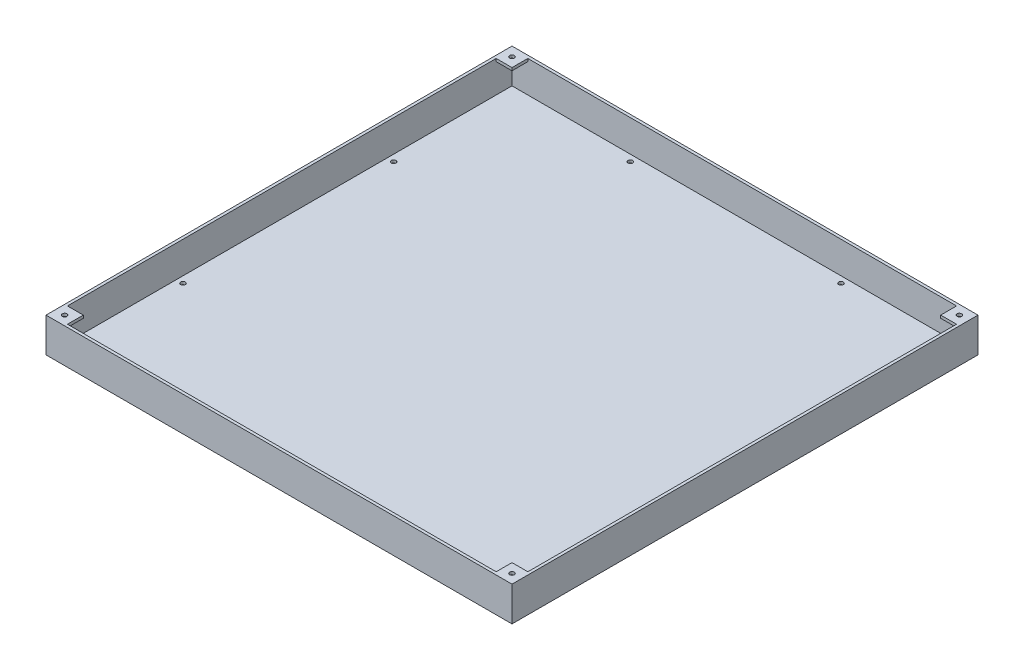
SolidWorks part; units mm, degrees
material "6063-O"
ref_plane "Front Plane" through (0, 0, 0) normal (0, 0, 1) x (1, 0, 0)
ref_plane "Top Plane" through (0, 0, 0) normal (0, 1, 0) x (1, 0, 0)
ref_plane "Right Plane" through (0, 0, 0) normal (1, 0, 0) x (0, 0, -1)
sketch "Sketch1" plane through (0, 0, 0) normal (0, 1, 0) x (1, 0, 0)
  line L1 (-250, 250) -> (250, 250)
  line L2 (-250, 250) -> (-250, -250)
  line L3 (-250, -250) -> (250, -250)
  line L4 (250, 250) -> (250, -250)
  line L5 (-250, 250) -> (250, -250) construction
  line L6 (-250, -250) -> (250, 250) construction
  point P0 (0, 0)
  dimension "D1" = 500
  dimension "D2" = 500
extrude "Boss-Extrude1" add sketch "Sketch1" along normal blind 37
shell "Shell1" thickness 3
sketch "Sketch3" plane through (0, 37, 0) normal (0, 1, 0) x (1, 0, 0)
  line L0 (-250, -250) -> (250, -250) construction
  line L1 (250, -250) -> (250, 250) construction
  line L2 (0, -250) -> (0, 250) construction
  line L3 (250, 250) -> (-250, 250) construction
  line L6 (-250, -250) -> (250, 250) construction
  line L7 (-250, 250) -> (250, -250) construction
  circle A0 centre (113, -240) radius 2.5
  circle A1 centre (-113, -240) radius 2.5
  circle A2 centre (240, 113) radius 2.5
  circle A3 centre (240, -113) radius 2.5
  circle A4 centre (-240, -113) radius 2.5
  circle A5 centre (-240, 113) radius 2.5
  circle A6 centre (-113, 240) radius 2.5
  circle A7 centre (113, 240) radius 2.5
  dimension "D1" = 5
  dimension "D2" = 10
  dimension "D3" = 137
extrude "Cut-Extrude1" cut sketch "Sketch3" against normal up to surface (37 mm away) up to face at (0, 0, 0)
sketch "Sketch4" plane through (0, 37, 0) normal (0, 1, 0) x (1, 0, 0)
  line L0 (0, 247) -> (0, 0) construction
  line L1 (-247, 247) -> (-230, 247)
  line L2 (-247, 247) -> (-247, 230)
  line L3 (-247, 230) -> (-230, 230)
  line L4 (-230, 247) -> (-230, 230)
  line L5 (247, 247) -> (-247, 247) construction
  line L6 (0, 0) -> (-247, 0) construction
  line L7 (-247, 247) -> (-247, -247) construction
  line L8 (247, 230) -> (230, 230)
  line L9 (230, 247) -> (230, 230)
  line L10 (247, 247) -> (230, 247)
  line L11 (247, 247) -> (247, 230)
  line L12 (247, -247) -> (247, -230)
  line L13 (247, -247) -> (230, -247)
  line L14 (230, -247) -> (230, -230)
  line L15 (247, -230) -> (230, -230)
  line L16 (-247, -230) -> (-230, -230)
  line L17 (-230, -247) -> (-230, -230)
  line L18 (-247, -247) -> (-230, -247)
  line L19 (-247, -247) -> (-247, -230)
  dimension "D1" = 17
  dimension "D2" = 17
extrude "Boss-Extrude2" add sketch "Sketch4" against normal blind 3
sketch "Sketch5" plane through (0, 37, 0) normal (0, 1, 0) x (1, 0, 0)
  line L0 (-230, 230) -> (-230, 247) construction
  line L1 (-247, 230) -> (-230, 230) construction
  line L2 (0, 247) -> (0, 0) construction
  line L3 (247, 247) -> (-247, 247) construction
  line L4 (0, 0) -> (-247, 0) construction
  line L5 (-247, 230) -> (-247, -230) construction
  circle A0 centre (-240, 240) radius 2.5
  circle A1 centre (240, 240) radius 2.5
  circle A2 centre (240, -240) radius 2.5
  circle A3 centre (-240, -240) radius 2.5
  dimension "D1" = 5
  dimension "D2" = 10
  dimension "D3" = 10
extrude "Cut-Extrude2" cut sketch "Sketch5" against normal up to vertex (3 mm away) up to point (230, 34, -230)
